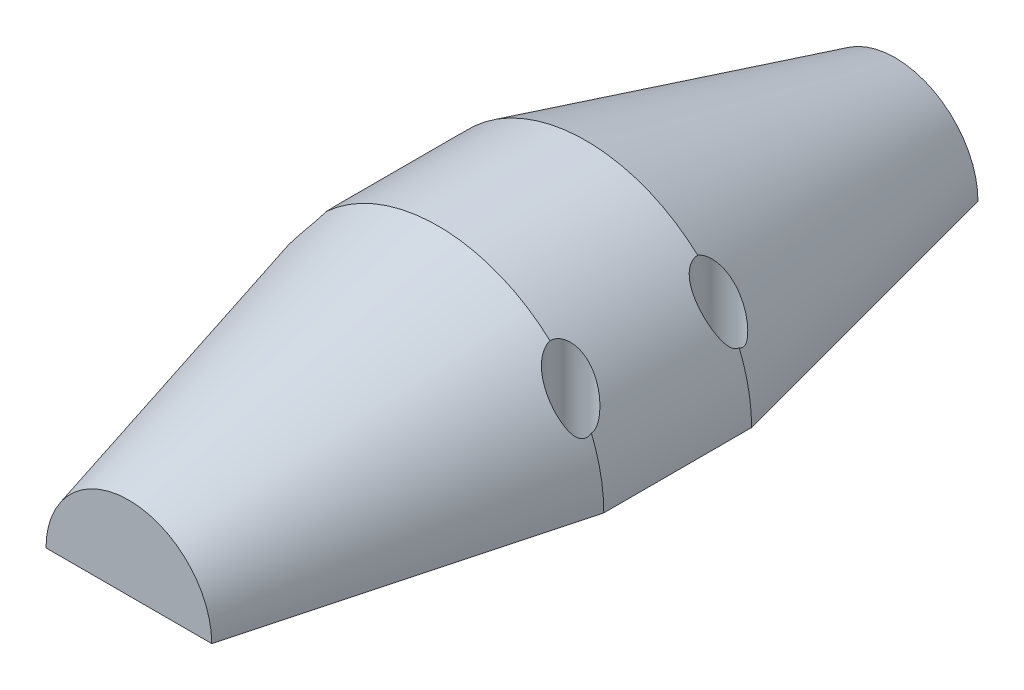
SolidWorks part; units mm, degrees
ref_plane "Front Plane" through (0, 0, 0) normal (0, 0, 1) x (1, 0, 0)
ref_plane "Top Plane" through (0, 0, 0) normal (0, 1, 0) x (1, 0, 0)
ref_plane "Right Plane" through (0, 0, 0) normal (1, 0, 0) x (0, 0, -1)
sketch "Sketch1" plane through (0, 0, 0) normal (0, 0, 1) x (1, 0, 0)
  circle A0 centre (0, 0) radius 12.7
extrude "Boss-Extrude1" add sketch "Sketch1" against normal blind 58.7248
ref_plane "Plane2" through (0, 0, -29.3624) normal (0, 0, -1) x (-1, 0, 0)
chamfer "Chamfer3" distance 6.35 angle 75 1 edges at (12.7, 0, -58.7248)
chamfer "Chamfer4" distance 6.35 angle 75 1 edges at (12.7, 0, 0)
sketch "Sketch2" plane through (0, 0, 0) normal (0, 1, 0) x (1, 0, 0)
  line L0 (-6.35, 0) -> (-12.7, 23.6985)
  line L1 (-12.7, 23.6985) -> (-12.7, 35.0263)
  line L2 (-12.7, 35.0263) -> (-6.35, 58.7248)
  line L3 (-6.35, 58.7248) -> (6.35, 58.7248)
  line L4 (6.35, 58.7248) -> (12.7, 35.0263)
  line L5 (12.7, 35.0263) -> (12.7, 23.6985)
  line L6 (12.7, 23.6985) -> (6.35, 0)
  line L7 (6.35, 0) -> (-6.35, 0)
extrude "Cut-Extrude1" cut sketch "Sketch2" against normal blind 58.7248
sketch "Sketch3" plane through (0, 0, 0) normal (0, 1, 0) x (1, 0, 0)
  line L0 (-12.7, 29.3624) -> (12.7, 29.3624) construction
  line L1 (0, 35.0263) -> (0, 58.7248) construction
  line L2 (6.35, 58.7248) -> (-6.35, 58.7248) construction
  line L3 (0, 35.0263) -> (-10.16, 35.0263) construction
  line L4 (-12.7, 35.0263) -> (-12.7, 23.6985) construction
  line L5 (12.7, 23.6985) -> (12.7, 35.0263) construction
  circle A0 centre (-10.16, 35.0263) radius 1.5875
  circle A1 centre (10.16, 35.0263) radius 1.5875
  circle A2 centre (10.16, 23.6985) radius 1.5875
  circle A3 centre (-10.16, 23.6985) radius 1.5875
extrude "Cut-Extrude2" cut sketch "Sketch3" along normal through all
